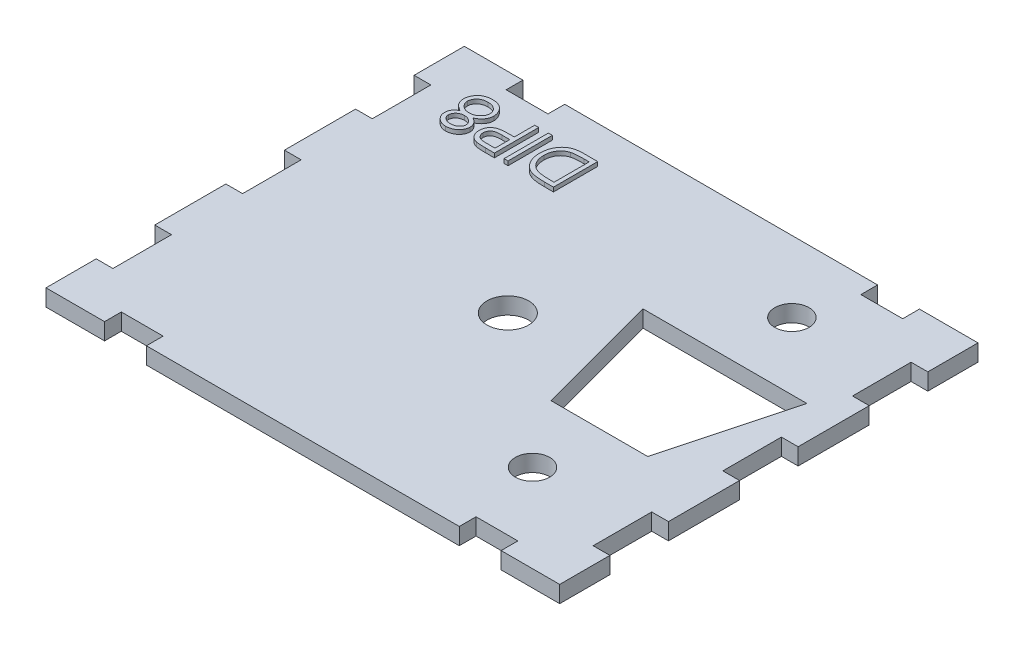
SolidWorks part; units mm, degrees
ref_plane "Front Plane" through (0, 0, 0) normal (0, 0, 1) x (1, 0, 0)
ref_plane "Top Plane" through (0, 0, 0) normal (0, 1, 0) x (1, 0, 0)
ref_plane "Right Plane" through (0, 0, 0) normal (1, 0, 0) x (0, 0, -1)
sketch "Sketch2" plane through (0, 0, 0) normal (0, 1, 0) x (1, 0, 0)
  line L1 (-50, 25) -> (50, 25)
  line L2 (-50, 25) -> (-50, -25)
  line L3 (-50, -25) -> (50, -25)
  line L4 (50, 25) -> (50, -25)
  line L5 (-50, 25) -> (50, -25) construction
  line L6 (-50, -25) -> (50, 25) construction
  point P0 (0, 0)
  dimension "D1" = 100
  dimension "D2" = 50
extrude "Boss-Extrude1" add sketch "Sketch2" along normal blind 2
sketch "Sketch12" plane through (0, 2, 0) normal (0, 1, 0) x (1, 0, 0)
  line L0 (-50, -25) -> (50, -25) construction
  line L1 (-40.2, -25) -> (-50, -25)
  line L2 (-40.2, -25) -> (-40.2, 25)
  line L3 (-40.2, 25) -> (-50, 25)
  line L4 (-50, -25) -> (-50, 25)
  line L5 (-50, -25) -> (50, -25) construction
  line L6 (41.2, -25) -> (50, -25)
  line L7 (41.2, -25) -> (41.2, 25)
  line L8 (41.2, 25) -> (50, 25)
  line L9 (50, -25) -> (50, 25)
extrude "Cut-Extrude8" cut sketch "Sketch12" against normal blind 6
sketch "Sketch13" plane through (0, 2, 0) normal (0, 1, 0) x (1, 0, 0)
  line L1 (-28.2, 19) -> (-30.2, 19)
  line L2 (-28.2, 19) -> (-28.2, 12)
  line L3 (-28.2, 12) -> (-30.2, 12)
  line L4 (-30.2, 19) -> (-30.2, 12)
  line L5 (-28.2, 3.5) -> (-30.2, 3.5)
  line L6 (-28.2, 3.5) -> (-28.2, -3.5)
  line L7 (-28.2, -3.5) -> (-30.2, -3.5)
  line L8 (-30.2, 3.5) -> (-30.2, -3.5)
  line L9 (-28.2, -12) -> (-30.2, -12)
  line L10 (-28.2, -12) -> (-28.2, -19)
  line L11 (-28.2, -19) -> (-30.2, -19)
  line L12 (-30.2, -12) -> (-30.2, -19)
  line L13 (29.2, 19) -> (31.2, 19)
  line L14 (29.2, 19) -> (29.2, 12)
  line L15 (29.2, 12) -> (31.2, 12)
  line L16 (31.2, 19) -> (31.2, 12)
  line L17 (29.2, 3.5) -> (31.2, 3.5)
  line L18 (29.2, 3.5) -> (29.2, -3.5)
  line L19 (29.2, -3.5) -> (31.2, -3.5)
  line L20 (31.2, 3.5) -> (31.2, -3.5)
  line L21 (29.2, -12) -> (31.2, -12)
  line L22 (29.2, -12) -> (29.2, -19)
  line L23 (29.2, -19) -> (31.2, -19)
  line L24 (31.2, -12) -> (31.2, -19)
  line L25 (-40.2, -25) -> (41.2, -25) construction
  line L26 (-23.2, 25) -> (-18.2, 25)
  line L27 (41.2, 25) -> (-40.2, 25) construction
  line L28 (-40.2, -25) -> (41.2, -25) construction
  line L29 (41.2, 25) -> (-40.2, 25) construction
  line L30 (-40.2, -25) -> (41.2, -25) construction
  line L31 (41.2, 25) -> (31.2, 25)
  line L32 (41.2, 25) -> (41.2, -25)
  line L33 (41.2, -25) -> (31.2, -25)
  line L34 (31.2, 25) -> (31.2, -25)
  line L35 (41.2, 25) -> (-40.2, 25) construction
  line L36 (-40.2, -25) -> (-30.2, -25)
  line L37 (-40.2, -25) -> (-40.2, 25)
  line L38 (-40.2, 25) -> (-30.2, 25)
  line L39 (-30.2, -25) -> (-30.2, 25)
  line L40 (-23.2, 25) -> (-23.2, 23)
  line L41 (-23.2, 23) -> (-18.2, 23)
  line L42 (-18.2, 25) -> (-18.2, 23)
  line L43 (-23.2, -25) -> (-18.2, -25)
  line L44 (-23.2, -25) -> (-23.2, -23)
  line L45 (-23.2, -23) -> (-18.2, -23)
  line L46 (-18.2, -25) -> (-18.2, -23)
  line L47 (24.2, -25) -> (19.2, -25)
  line L48 (24.2, -25) -> (24.2, -23)
  line L49 (24.2, -23) -> (19.2, -23)
  line L50 (19.2, -25) -> (19.2, -23)
  line L51 (24.2, 25) -> (19.2, 25)
  line L52 (24.2, 25) -> (24.2, 23)
  line L53 (24.2, 23) -> (19.2, 23)
  line L54 (19.2, 25) -> (19.2, 23)
  point P24 (29.2, 0)
  point P30 (30.2, 3.5)
  line M32 (41.2, -25) -> (41.2, 25)
  line M41 (41.2, 25) -> (-40.2, 25)
  line M42 (-40.2, 25) -> (-40.2, -25)
  line M47 (-40.2, -25) -> (41.2, -25)
  dimension "D1" = 2
  dimension "D2" = 2
  dimension "D3" = 2
  dimension "D4" = 2
  dimension "D5" = 2
  dimension "D6" = 2
  dimension "D7" = 57.4
  dimension "D8" = 57.4
  dimension "D9" = 57.4
  dimension "D10" = 7
  dimension "D11" = 7
  dimension "D12" = 7
  dimension "D13" = 7
  dimension "D14" = 7
  dimension "D15" = 7
  dimension "D16" = 5
  dimension "D17" = 2
  dimension "D18" = 5
  dimension "D19" = 6
  dimension "D20" = 8.5
  dimension "D21" = 8.5
  dimension "D22" = 6
  dimension "D23" = 6
  dimension "D24" = 8.5
  dimension "D25" = 8.5
  dimension "D26" = 6
  dimension "D27" = 5
  dimension "D28" = 5
  dimension "D29" = 2
  dimension "D30" = 2
  dimension "D31" = 5
  dimension "D32" = 5
  dimension "D33" = 5
  dimension "D34" = 5
  dimension "D35" = 2
extrude "Cut-Extrude10" cut sketch "Sketch13" against normal blind 6 contours L5 L8 L7 L6 | L39 L12 L8 L4 M47 M41 M42 | L1 L4 L3 L2 | L50 L48 L49 M47 | L24 L21 L22 L23 | L20 L17 L18 L19 | L16 L13 L14 L15 | L54 L53 L52 M41 | L9 L12 L11 L10 | L34 L16 L20 L24 M41 M47 M32 | L26 L42 L41 L40 | L45 L46 L43 L44
sketch "Sketch15" plane through (0, 0, 0) normal (0, -1, 0) x (1, 0, 0)
  line L0 (24.2, 23) -> (19.2, 23) construction
  line L16 (20.7242, -7.5) -> (20.7242, -8.5)
  line L17 (20.7242, -7.5) -> (25.936, -7.5)
  line L18 (25.936, -7.5) -> (22.4527, 5.5)
  line L19 (22.4527, 5.5) -> (12.4527, 5.5)
  line L20 (12.4527, 5.5) -> (8.9693, -7.5)
  line L21 (8.9693, -7.5) -> (14.1811, -7.5)
  line L22 (14.1811, -7.5) -> (14.1811, -8.5)
  line L23 (14.1811, -8.5) -> (7.6661, -8.5)
  line L24 (7.6661, -8.5) -> (11.6853, 6.5)
  line L25 (11.6853, 6.5) -> (23.22, 6.5)
  line L26 (23.22, 6.5) -> (27.2392, -8.5)
  line L27 (27.2392, -8.5) -> (20.7242, -8.5)
  line L28 (20.7242, -8.5) -> (14.1811, -8.5)
  line L29 (14.1811, -7.5) -> (20.7242, -7.5)
  line L31 (29.2, 12) -> (29.2, 19) construction
  dimension "D4" = 16.5
  dimension "D18" = 11.5347
  dimension "D19" = 15.5291
  dimension "D20" = 15.5291
  dimension "D21" = 13.4586
  dimension "D22" = 13.4586
  dimension "D23" = 10
  dimension "D24" = 5.2118
  dimension "D25" = 5.2118
  dimension "D26" = 6.515
  dimension "D27" = 6.515
  dimension "D28" = 1
  dimension "D29" = 105
  dimension "D30" = 105
  dimension "D31" = 75
  dimension "D32" = 75
  dimension "D33" = 5.98
  dimension "D34" = 1
extrude "Cut-Extrude13" cut sketch "Sketch15" against normal blind 10 contours L21 L29 L17 L18 L19 L20 | L27 L26 L25 L24 L23 L22 L21 L20 L19 L18 L17 L16 | L29 L22 L28 L16
sketch "Sketch16" plane through (0, 0, 0) normal (0, -1, 0) x (-1, 0, 0)
  circle A0 centre (0, 0) radius 2.5
  dimension "D1" = 5
extrude "Cut-Extrude14" cut sketch "Sketch16" against normal blind 10 contours A0
sketch "Sketch17" plane through (0, 0, 0) normal (0, -1, 0) x (-1, 0, 0)
  line L2 (-27.2392, 8.5) -> (-7.6661, 8.5) construction
  line L4 (-11.6853, -6.5) -> (-23.22, -6.5) construction
  circle A0 centre (-17.4527, -14.5) radius 2.05
  circle A1 centre (-17.4527, 16.5) radius 2.05
  dimension "D1" = 4.1
  dimension "D2" = 4.1
  dimension "D3" = 8
  dimension "D4" = 9.7866
  dimension "D5" = 9.7866
  dimension "D6" = 5.7673
  dimension "D7" = 5.7673
  dimension "D8" = 8
extrude "Cut-Extrude15" cut sketch "Sketch17" against normal blind 3.5
sketch "Sketch22" plane through (0, 2, 0) normal (0, 1, 0) x (1, 0, 0)
  line L0 (-24.5837, 20.5398) -> (4.8961, 20.5398) construction
  text T0 "DIP8" font "Century Gothic" height in points 20
extrude "Boss-Extrude4" add sketch "Sketch22" along normal blind 0.5
